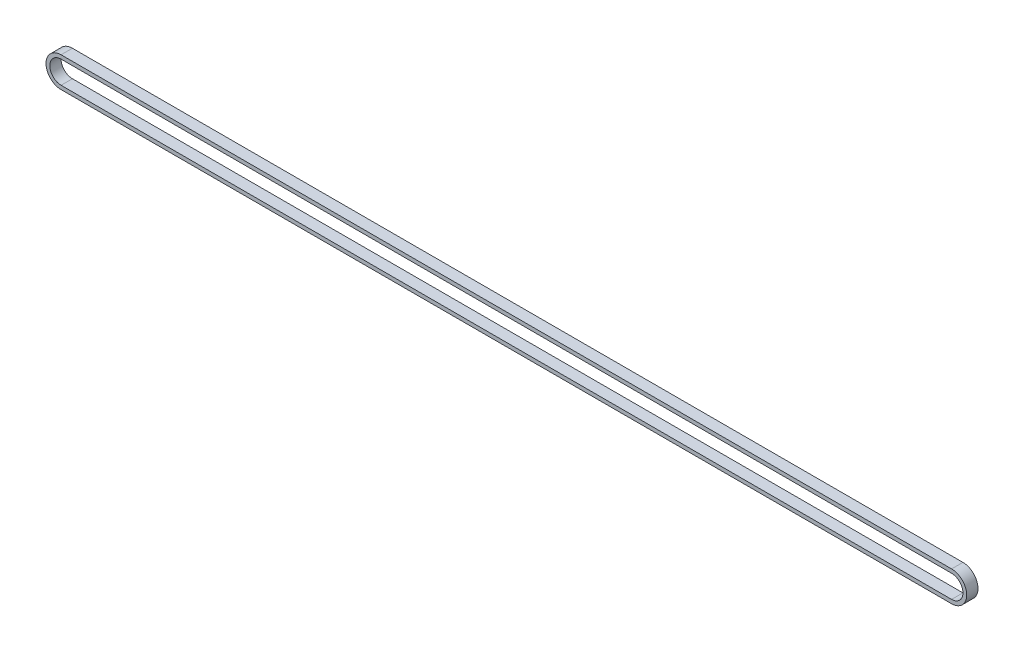
SolidWorks part; units mm, degrees
ref_plane "前视基准面" through (0, 0, 0) normal (0, 0, 1) x (1, 0, 0)
ref_plane "上视基准面" through (0, 0, 0) normal (0, 1, 0) x (1, 0, 0)
ref_plane "右视基准面" through (0, 0, 0) normal (1, 0, 0) x (0, 0, -1)
sketch "Sketch1" plane through (0, 0, 0) normal (0, 0, 1) x (1, 0, 0)
  line L0 (0, 0) -> (0, 49.0139) construction
  line L1 (-236, 6) -> (236, 6)
  line L3 (236, 8) -> (-236, 8)
  line L5 (-236, -6) -> (236, -6)
  line L7 (236, -8) -> (-236, -8)
  arc A0 (-236, 8) -> (-236, -8) centre (-236, 0) ccw
  arc A1 (-236, 6) -> (-236, -6) centre (-236, 0) ccw
  arc A2 (236, 6) -> (236, -6) centre (236, 0) cw
  arc A3 (236, 8) -> (236, -8) centre (236, 0) cw
  dimension "D1" = 2
  dimension "D2" = 12
  dimension "D3" = 236
extrude "Boss-Extrude1" add sketch "Sketch1" along normal blind 6
